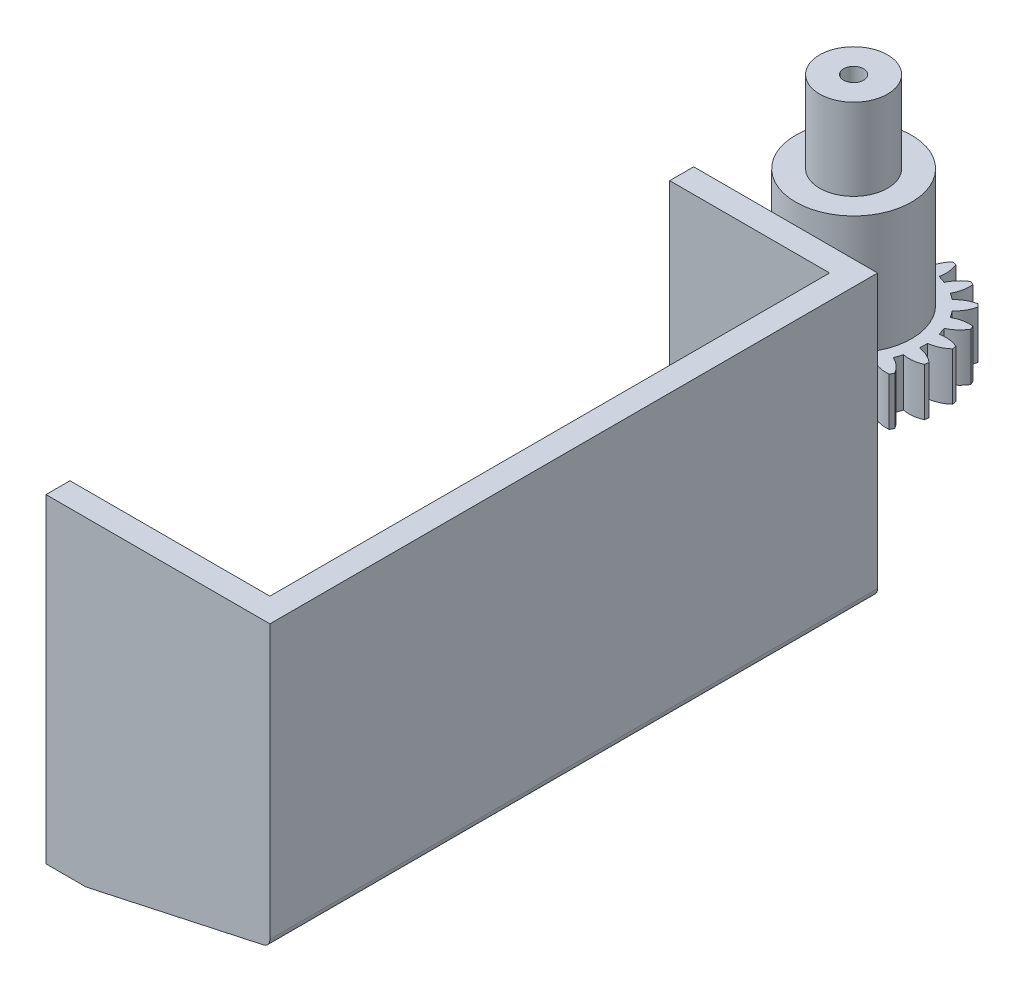
SolidWorks part; units mm, degrees
ref_plane "前视基准面" through (0, 0, 0) normal (0, 0, 1) x (1, 0, 0)
ref_plane "上视基准面" through (0, 0, 0) normal (0, 1, 0) x (1, 0, 0)
ref_plane "右视基准面" through (0, 0, 0) normal (1, 0, 0) x (0, 0, -1)
sketch "草图1" plane through (0, 0, 0) normal (0, 1, 0) x (1, 0, 0)
  line L0 (-5, 0) -> (-5, -18)
  line L10 (-5, -18) -> (15, -18)
  line L11 (15, -18) -> (15, -88)
  line L12 (15, -88) -> (-10, -88)
  line L13 (-10, -88) -> (-10, -91)
  line L14 (-10, -91) -> (18, -91)
  line L15 (18, -91) -> (18, -15)
  line L16 (18, -15) -> (5, -15)
  line L17 (5, -15) -> (5, 0)
  arc A2 (5, 0) -> (-5, 0) centre (0, 0) ccw
  arc A3 (-5, 0) -> (5, 0) centre (0, 0) ccw construction
  dimension "D1" = 10
  dimension "D2" = 3
  dimension "D3" = 3
  dimension "D4" = 3
  dimension "D5" = 70
  dimension "D6" = 10
  dimension "D7" = 25
  dimension "D8" = 15
extrude "凸台-拉伸1" add sketch "草图1" against normal blind 6
sketch "草图2" plane through (0, 0, 0) normal (0, 1, 0) x (1, 0, 0)
  line L15 (-5, -18) -> (15, -18) construction
  line L16 (18, -91) -> (18, -15) construction
  line L17 (15, -18) -> (15, -88) construction
  line L18 (-10, -91) -> (18, -91) construction
  line L19 (15, -88) -> (-10, -88) construction
  line L20 (-10, -88) -> (-10, -91) construction
  line L21 (-5, -18) -> (15, -18)
  line L22 (18, -91) -> (18, -15)
  line L23 (15, -18) -> (15, -88)
  line L24 (-10, -91) -> (18, -91)
  line L25 (15, -88) -> (-10, -88)
  line L26 (-10, -88) -> (-10, -91)
  line L27 (18, -15) -> (-5, -15)
  line L28 (-5, 0) -> (-5, -18) construction
  line L29 (-5, -15) -> (-5, -18)
extrude "凸台-拉伸2" add sketch "草图2" along normal mid plane 40
sketch "草图4" plane through (0, -6, 0) normal (0, -1, 0) x (1, 0, 0)
  arc A80 (-0.5047, 8.7344) -> (-1.471, 10.9012) centre (-4.4767, 8.262) ccw
  arc A81 (-1.471, 10.9012) -> (-1.9816, 10.82) centre (0, 0) ccw
  arc A82 (-1.9816, 10.82) -> (-2.2284, 8.4605) centre (1.6943, 9.2429) ccw
  arc A83 (-2.2284, 8.4605) -> (-3.1791, 8.151) centre (0, 0) ccw
  arc A84 (-3.1791, 8.151) -> (-4.7676, 9.9131) centre (-6.8107, 6.4743) ccw
  arc A85 (-4.7676, 9.9131) -> (-5.2282, 9.6781) centre (0, 0) ccw
  arc A86 (-5.2282, 9.6781) -> (-4.7337, 7.3578) centre (-1.2448, 9.3141) ccw
  arc A87 (-4.7337, 7.3578) -> (-5.5423, 6.7696) centre (0, 0) ccw
  arc A88 (-5.5423, 6.7696) -> (-7.5976, 7.9547) centre (-8.4781, 4.0528) ccw
  arc A89 (-7.5976, 7.9547) -> (-7.963, 7.5888) centre (0, 0) ccw
  arc A90 (-7.963, 7.5888) -> (-6.7757, 5.5348) centre (-4.0621, 8.4736) ccw
  arc A91 (-6.7757, 5.5348) -> (-7.363, 4.7256) centre (0, 0) ccw
  arc A92 (-7.363, 4.7256) -> (-9.6839, 5.2175) centre (-9.3155, 1.2345) ccw
  arc A93 (-9.6839, 5.2175) -> (-9.9184, 4.7567) centre (0, 0) ccw
  arc A94 (-9.9184, 4.7567) -> (-8.1545, 3.1701) centre (-6.4818, 6.8036) ccw
  arc A95 (-8.1545, 3.1701) -> (-8.4629, 2.2191) centre (0, 0) ccw
  arc A96 (-8.4629, 2.2191) -> (-10.8222, 1.9697) centre (-9.241, -1.7045) ccw
  arc A97 (-10.8222, 1.9697) -> (-10.9028, 1.459) centre (0, 0) ccw
  arc A98 (-10.9028, 1.459) -> (-8.735, 0.4951) centre (-8.2669, 4.4676) ccw
  arc A99 (-8.735, 0.4951) -> (-8.7344, -0.5047) centre (0, 0) ccw
  arc A100 (-8.7344, -0.5047) -> (-10.9012, -1.471) centre (-8.262, -4.4767) ccw
  arc A101 (-10.9012, -1.471) -> (-10.82, -1.9816) centre (0, 0) ccw
  arc A102 (-10.82, -1.9816) -> (-8.4605, -2.2284) centre (-9.2429, 1.6943) ccw
  arc A103 (-8.4605, -2.2284) -> (-8.151, -3.1791) centre (0, 0) ccw
  arc A104 (-8.151, -3.1791) -> (-9.9131, -4.7676) centre (-6.4743, -6.8107) ccw
  arc A105 (-9.9131, -4.7676) -> (-9.6781, -5.2282) centre (0, 0) ccw
  arc A106 (-9.6781, -5.2282) -> (-7.3578, -4.7337) centre (-9.3141, -1.2448) ccw
  arc A107 (-7.3578, -4.7337) -> (-6.7696, -5.5423) centre (0, 0) ccw
  arc A108 (-6.7696, -5.5423) -> (-7.9547, -7.5976) centre (-4.0528, -8.4781) ccw
  arc A109 (-7.9547, -7.5976) -> (-7.5888, -7.963) centre (0, 0) ccw
  arc A110 (-7.5888, -7.963) -> (-5.5348, -6.7757) centre (-8.4736, -4.0621) ccw
  arc A111 (-5.5348, -6.7757) -> (-4.7256, -7.363) centre (0, 0) ccw
  arc A112 (-4.7256, -7.363) -> (-5.2175, -9.6839) centre (-1.2345, -9.3155) ccw
  arc A113 (-5.2175, -9.6839) -> (-4.7567, -9.9184) centre (0, 0) ccw
  arc A114 (-4.7567, -9.9184) -> (-3.1701, -8.1545) centre (-6.8036, -6.4818) ccw
  arc A115 (-3.1701, -8.1545) -> (-2.2191, -8.4629) centre (0, 0) ccw
  arc A116 (-2.2191, -8.4629) -> (-1.9697, -10.8222) centre (1.7045, -9.241) ccw
  arc A117 (-1.9697, -10.8222) -> (-1.459, -10.9028) centre (0, 0) ccw
  arc A118 (-1.459, -10.9028) -> (-0.4951, -8.735) centre (-4.4676, -8.2669) ccw
  arc A119 (-0.4951, -8.735) -> (0.5047, -8.7344) centre (0, 0) ccw
  arc A120 (0.5047, -8.7344) -> (1.471, -10.9012) centre (4.4767, -8.262) ccw
  arc A121 (1.471, -10.9012) -> (1.9816, -10.82) centre (0, 0) ccw
  arc A122 (1.9816, -10.82) -> (2.2284, -8.4605) centre (-1.6943, -9.2429) ccw
  arc A123 (2.2284, -8.4605) -> (3.1791, -8.151) centre (0, 0) ccw
  arc A124 (3.1791, -8.151) -> (4.7676, -9.9131) centre (6.8107, -6.4743) ccw
  arc A125 (4.7676, -9.9131) -> (5.2282, -9.6781) centre (0, 0) ccw
  arc A126 (5.2282, -9.6781) -> (4.7337, -7.3578) centre (1.2448, -9.3141) ccw
  arc A127 (4.7337, -7.3578) -> (5.5423, -6.7696) centre (0, 0) ccw
  arc A128 (5.5423, -6.7696) -> (7.5976, -7.9547) centre (8.4781, -4.0528) ccw
  arc A129 (7.5976, -7.9547) -> (7.963, -7.5888) centre (0, 0) ccw
  arc A130 (7.963, -7.5888) -> (6.7757, -5.5348) centre (4.0621, -8.4736) ccw
  arc A131 (6.7757, -5.5348) -> (7.363, -4.7256) centre (0, 0) ccw
  arc A132 (7.363, -4.7256) -> (9.6839, -5.2175) centre (9.3155, -1.2345) ccw
  arc A133 (9.6839, -5.2175) -> (9.9184, -4.7567) centre (0, 0) ccw
  arc A134 (9.9184, -4.7567) -> (8.1545, -3.1701) centre (6.4818, -6.8036) ccw
  arc A135 (8.1545, -3.1701) -> (8.4629, -2.2191) centre (0, 0) ccw
  arc A136 (8.4629, -2.2191) -> (10.8222, -1.9697) centre (9.241, 1.7045) ccw
  arc A137 (10.8222, -1.9697) -> (10.9028, -1.459) centre (0, 0) ccw
  arc A138 (10.9028, -1.459) -> (8.735, -0.4951) centre (8.2669, -4.4676) ccw
  arc A139 (8.735, -0.4951) -> (8.7344, 0.5047) centre (0, 0) ccw
  arc A140 (8.7344, 0.5047) -> (10.9012, 1.471) centre (8.262, 4.4767) ccw
  arc A141 (10.9012, 1.471) -> (10.82, 1.9816) centre (0, 0) ccw
  arc A142 (10.82, 1.9816) -> (8.4605, 2.2284) centre (9.2429, -1.6943) ccw
  arc A143 (8.4605, 2.2284) -> (8.151, 3.1791) centre (0, 0) ccw
  arc A144 (8.151, 3.1791) -> (9.9131, 4.7676) centre (6.4743, 6.8107) ccw
  arc A145 (9.9131, 4.7676) -> (9.6781, 5.2282) centre (0, 0) ccw
  arc A146 (9.6781, 5.2282) -> (7.3578, 4.7337) centre (9.3141, 1.2448) ccw
  arc A147 (7.3578, 4.7337) -> (6.7696, 5.5423) centre (0, 0) ccw
  arc A148 (6.7696, 5.5423) -> (7.9547, 7.5976) centre (4.0528, 8.4781) ccw
  arc A149 (7.9547, 7.5976) -> (7.5888, 7.963) centre (0, 0) ccw
  arc A150 (7.5888, 7.963) -> (5.5348, 6.7757) centre (8.4736, 4.0621) ccw
  arc A151 (5.5348, 6.7757) -> (4.7256, 7.363) centre (0, 0) ccw
  arc A152 (4.7256, 7.363) -> (5.2175, 9.6839) centre (1.2345, 9.3155) ccw
  arc A153 (5.2175, 9.6839) -> (4.7567, 9.9184) centre (0, 0) ccw
  arc A154 (4.7567, 9.9184) -> (3.1701, 8.1545) centre (6.8036, 6.4818) ccw
  arc A155 (3.1701, 8.1545) -> (2.2191, 8.4629) centre (0, 0) ccw
  arc A156 (2.2191, 8.4629) -> (1.9697, 10.8222) centre (-1.7045, 9.241) ccw
  arc A157 (1.9697, 10.8222) -> (1.459, 10.9028) centre (0, 0) ccw
  arc A158 (1.459, 10.9028) -> (0.4951, 8.735) centre (4.4676, 8.2669) ccw
  arc A159 (0.4951, 8.735) -> (-0.5047, 8.7344) centre (0, 0) ccw
  arc A160 (-0.5047, 8.7344) -> (-1.471, 10.9012) centre (-4.4767, 8.262) ccw
  arc A161 (-1.471, 10.9012) -> (-1.9816, 10.82) centre (0, 0) ccw
  arc A162 (-1.9816, 10.82) -> (-2.2284, 8.4605) centre (1.6943, 9.2429) ccw
  arc A163 (-2.2284, 8.4605) -> (-3.1791, 8.151) centre (0, 0) ccw
  arc A164 (-3.1791, 8.151) -> (-4.7676, 9.9131) centre (-6.8107, 6.4743) ccw
  arc A165 (-4.7676, 9.9131) -> (-5.2282, 9.6781) centre (0, 0) ccw
  arc A166 (-5.2282, 9.6781) -> (-4.7337, 7.3578) centre (-1.2448, 9.3141) ccw
  arc A167 (-4.7337, 7.3578) -> (-5.5423, 6.7696) centre (0, 0) ccw
  arc A168 (-5.5423, 6.7696) -> (-7.5976, 7.9547) centre (-8.4781, 4.0528) ccw
  arc A169 (-7.5976, 7.9547) -> (-7.963, 7.5888) centre (0, 0) ccw
  arc A170 (-7.963, 7.5888) -> (-6.7757, 5.5348) centre (-4.0621, 8.4736) ccw
  arc A171 (-6.7757, 5.5348) -> (-7.363, 4.7256) centre (0, 0) ccw
  arc A172 (-7.363, 4.7256) -> (-9.6839, 5.2175) centre (-9.3155, 1.2345) ccw
  arc A173 (-9.6839, 5.2175) -> (-9.9184, 4.7567) centre (0, 0) ccw
  arc A174 (-9.9184, 4.7567) -> (-8.1545, 3.1701) centre (-6.4818, 6.8036) ccw
  arc A175 (-8.1545, 3.1701) -> (-8.4629, 2.2191) centre (0, 0) ccw
  arc A176 (-8.4629, 2.2191) -> (-10.8222, 1.9697) centre (-9.241, -1.7045) ccw
  arc A177 (-10.8222, 1.9697) -> (-10.9028, 1.459) centre (0, 0) ccw
  arc A178 (-10.9028, 1.459) -> (-8.735, 0.4951) centre (-8.2669, 4.4676) ccw
  arc A179 (-8.735, 0.4951) -> (-8.7344, -0.5047) centre (0, 0) ccw
  arc A180 (-8.7344, -0.5047) -> (-10.9012, -1.471) centre (-8.262, -4.4767) ccw
  arc A181 (-10.9012, -1.471) -> (-10.82, -1.9816) centre (0, 0) ccw
  arc A182 (-10.82, -1.9816) -> (-8.4605, -2.2284) centre (-9.2429, 1.6943) ccw
  arc A183 (-8.4605, -2.2284) -> (-8.151, -3.1791) centre (0, 0) ccw
  arc A184 (-8.151, -3.1791) -> (-9.9131, -4.7676) centre (-6.4743, -6.8107) ccw
  arc A185 (-9.9131, -4.7676) -> (-9.6781, -5.2282) centre (0, 0) ccw
  arc A186 (-9.6781, -5.2282) -> (-7.3578, -4.7337) centre (-9.3141, -1.2448) ccw
  arc A187 (-7.3578, -4.7337) -> (-6.7696, -5.5423) centre (0, 0) ccw
  arc A188 (-6.7696, -5.5423) -> (-7.9547, -7.5976) centre (-4.0528, -8.4781) ccw
  arc A189 (-7.9547, -7.5976) -> (-7.5888, -7.963) centre (0, 0) ccw
  arc A190 (-7.5888, -7.963) -> (-5.5348, -6.7757) centre (-8.4736, -4.0621) ccw
  arc A191 (-5.5348, -6.7757) -> (-4.7256, -7.363) centre (0, 0) ccw
  arc A192 (-4.7256, -7.363) -> (-5.2175, -9.6839) centre (-1.2345, -9.3155) ccw
  arc A193 (-5.2175, -9.6839) -> (-4.7567, -9.9184) centre (0, 0) ccw
  arc A194 (-4.7567, -9.9184) -> (-3.1701, -8.1545) centre (-6.8036, -6.4818) ccw
  arc A195 (-3.1701, -8.1545) -> (-2.2191, -8.4629) centre (0, 0) ccw
  arc A196 (-2.2191, -8.4629) -> (-1.9697, -10.8222) centre (1.7045, -9.241) ccw
  arc A197 (-1.9697, -10.8222) -> (-1.459, -10.9028) centre (0, 0) ccw
  arc A198 (-1.459, -10.9028) -> (-0.4951, -8.735) centre (-4.4676, -8.2669) ccw
  arc A199 (-0.4951, -8.735) -> (0.5047, -8.7344) centre (0, 0) ccw
  arc A200 (0.5047, -8.7344) -> (1.471, -10.9012) centre (4.4767, -8.262) ccw
  arc A201 (1.471, -10.9012) -> (1.9816, -10.82) centre (0, 0) ccw
  arc A202 (1.9816, -10.82) -> (2.2284, -8.4605) centre (-1.6943, -9.2429) ccw
  arc A203 (2.2284, -8.4605) -> (3.1791, -8.151) centre (0, 0) ccw
  arc A204 (3.1791, -8.151) -> (4.7676, -9.9131) centre (6.8107, -6.4743) ccw
  arc A205 (4.7676, -9.9131) -> (5.2282, -9.6781) centre (0, 0) ccw
  arc A206 (5.2282, -9.6781) -> (4.7337, -7.3578) centre (1.2448, -9.3141) ccw
  arc A207 (4.7337, -7.3578) -> (5.5423, -6.7696) centre (0, 0) ccw
  arc A208 (5.5423, -6.7696) -> (7.5976, -7.9547) centre (8.4781, -4.0528) ccw
  arc A209 (7.5976, -7.9547) -> (7.963, -7.5888) centre (0, 0) ccw
  arc A210 (7.963, -7.5888) -> (6.7757, -5.5348) centre (4.0621, -8.4736) ccw
  arc A211 (6.7757, -5.5348) -> (7.363, -4.7256) centre (0, 0) ccw
  arc A212 (7.363, -4.7256) -> (9.6839, -5.2175) centre (9.3155, -1.2345) ccw
  arc A213 (9.6839, -5.2175) -> (9.9184, -4.7567) centre (0, 0) ccw
  arc A214 (9.9184, -4.7567) -> (8.1545, -3.1701) centre (6.4818, -6.8036) ccw
  arc A215 (8.1545, -3.1701) -> (8.4629, -2.2191) centre (0, 0) ccw
  arc A216 (8.4629, -2.2191) -> (10.8222, -1.9697) centre (9.241, 1.7045) ccw
  arc A217 (10.8222, -1.9697) -> (10.9028, -1.459) centre (0, 0) ccw
  arc A218 (10.9028, -1.459) -> (8.735, -0.4951) centre (8.2669, -4.4676) ccw
  arc A219 (8.735, -0.4951) -> (8.7344, 0.5047) centre (0, 0) ccw
  arc A220 (8.7344, 0.5047) -> (10.9012, 1.471) centre (8.262, 4.4767) ccw
  arc A221 (10.9012, 1.471) -> (10.82, 1.9816) centre (0, 0) ccw
  arc A222 (10.82, 1.9816) -> (8.4605, 2.2284) centre (9.2429, -1.6943) ccw
  arc A223 (8.4605, 2.2284) -> (8.151, 3.1791) centre (0, 0) ccw
  arc A224 (8.151, 3.1791) -> (9.9131, 4.7676) centre (6.4743, 6.8107) ccw
  arc A225 (9.9131, 4.7676) -> (9.6781, 5.2282) centre (0, 0) ccw
  arc A226 (9.6781, 5.2282) -> (7.3578, 4.7337) centre (9.3141, 1.2448) ccw
  arc A227 (7.3578, 4.7337) -> (6.7696, 5.5423) centre (0, 0) ccw
  arc A228 (6.7696, 5.5423) -> (7.9547, 7.5976) centre (4.0528, 8.4781) ccw
  arc A229 (7.9547, 7.5976) -> (7.5888, 7.963) centre (0, 0) ccw
  arc A230 (7.5888, 7.963) -> (5.5348, 6.7757) centre (8.4736, 4.0621) ccw
  arc A231 (5.5348, 6.7757) -> (4.7256, 7.363) centre (0, 0) ccw
  arc A232 (4.7256, 7.363) -> (5.2175, 9.6839) centre (1.2345, 9.3155) ccw
  arc A233 (5.2175, 9.6839) -> (4.7567, 9.9184) centre (0, 0) ccw
  arc A234 (4.7567, 9.9184) -> (3.1701, 8.1545) centre (6.8036, 6.4818) ccw
  arc A235 (3.1701, 8.1545) -> (2.2191, 8.4629) centre (0, 0) ccw
  arc A236 (2.2191, 8.4629) -> (1.9697, 10.8222) centre (-1.7045, 9.241) ccw
  arc A237 (1.9697, 10.8222) -> (1.459, 10.9028) centre (0, 0) ccw
  arc A238 (1.459, 10.9028) -> (0.4951, 8.735) centre (4.4676, 8.2669) ccw
  arc A239 (0.4951, 8.735) -> (-0.5047, 8.7344) centre (0, 0) ccw
  point P0 (0, 0)
  dimension "D1" = 0
extrude "凸台-拉伸4" add sketch "草图4" against normal blind 6
sketch "草图5" plane through (0, 0, 0) normal (0, 1, 0) x (1, 0, 0)
  circle A0 centre (0, 0) radius 7.25
  dimension "D1" = 14.5
extrude "凸台-拉伸5" add sketch "草图5" along normal blind 14.8
sketch "草图6" plane through (0, 14.8, 0) normal (0, 1, 0) x (1, 0, 0)
  circle A0 centre (0, 0) radius 4.25
  circle A1 centre (0, 0) radius 1.25
  dimension "D1" = 8.5
  dimension "D2" = 2.5
extrude "凸台-拉伸6" add sketch "草图6" along normal blind 10.2
sketch "草图8" plane through (0, 0, 91) normal (0, 0, 1) x (1, 0, 0)
  line L0 (-10, -20) -> (18, -10)
  line L1 (18, -20) -> (18, 20) construction
  line L2 (-10, -20) -> (18, -20)
  line L3 (18, -20) -> (18, -10)
  dimension "D1" = 10
extrude "凸台-拉伸7" add sketch "草图8" against normal blind 76
sketch "草图9" plane through (0, 0, 15) normal (0, 0, -1) x (-1, 0, 0)
  line L0 (4.895, -19.9772) -> (-17.2124, -15.1712)
  line L1 (-18, -20) -> (10, -20) construction
  line L2 (-18, -20) -> (-18, 20) construction
  line L5 (-18, -14.194) -> (-18, -20)
  line L6 (-18, -20) -> (5.1074, -20)
  arc A0 (5.1074, -20) -> (4.895, -19.9772) centre (5.1074, -19) cw
  arc A1 (-17.2124, -15.1712) -> (-18, -14.194) centre (-17, -14.194) cw
  point P11 (5, -20)
  point P14 (-18, -15)
  dimension "D1" = 1
extrude "切除-拉伸1" cut sketch "草图9" against normal blind 76
